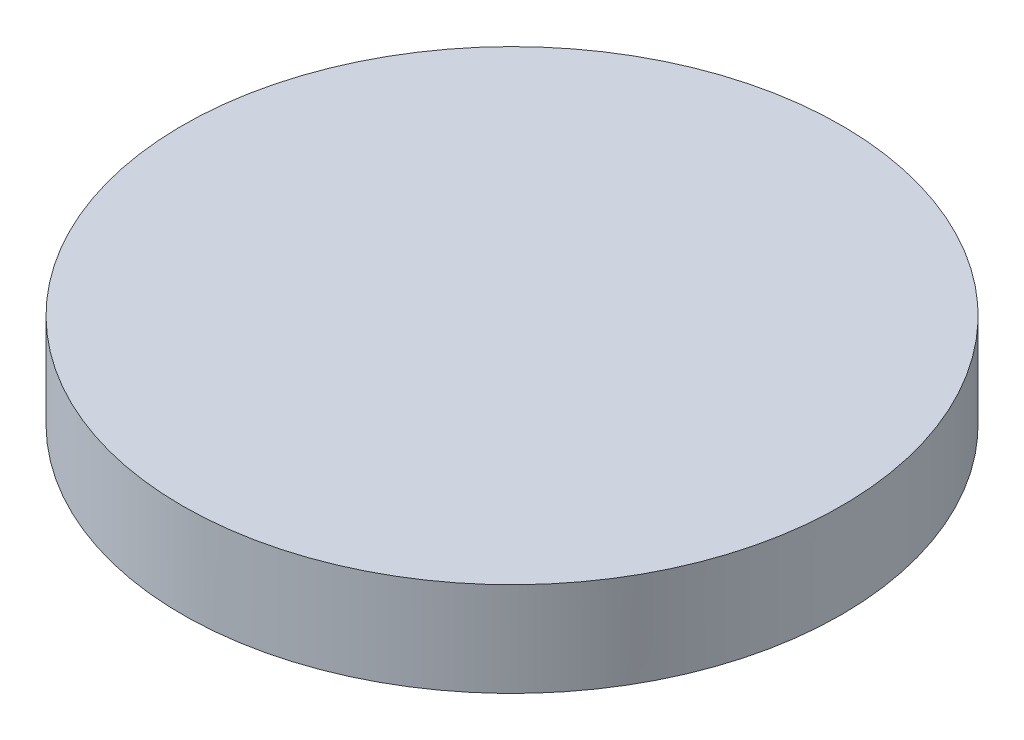
SolidWorks part; units mm, degrees
ref_plane "Front Plane" through (0, 0, 0) normal (0, 0, 1) x (1, 0, 0)
ref_plane "Top Plane" through (0, 0, 0) normal (0, 1, 0) x (1, 0, 0)
ref_plane "Right Plane" through (0, 0, 0) normal (1, 0, 0) x (0, 0, -1)
sketch "base" plane through (0, 0, 0) normal (0, 1, 0) x (1, 0, 0)
  circle A0 centre (0, 0) radius 28
extrude "extrusao_base" add sketch "base" along normal blind 8
sketch "corte_base" plane through (0, 0, 0) normal (0, 1, 0) x (1, 0, 0)
  circle A0 centre (0, 0) radius 26.5
extrude "extrusao_corte_base" cut sketch "corte_base" along normal blind 5
sketch "mid_line" plane through (0, 0, 0) normal (0, 1, 0) x (1, 0, 0)
  line L0 (-64.917, 0) -> (69.5719, 0) construction
ref_plane "Plane2" through (0, 0, 0) normal (0, 0, 1) x (1, 0, 0)
sketch "usb" plane through (0, 0, 0) normal (0, 1, 0) x (1, 0, 0)
  line L0 (-73.9689, 0) -> (73.9689, 0) construction
  line L1 (-142.5267, 5.1) -> (0, 5.1)
  line L2 (-142.5267, 5.1) -> (-142.5267, -5.1)
  line L3 (-142.5267, -5.1) -> (0, -5.1)
  line L4 (0, 5.1) -> (0, -5.1)
  line L5 (-142.5267, 5.1) -> (0, -5.1) construction
  line L6 (-142.5267, -5.1) -> (0, 5.1) construction
  point P0 (-71.2633, 0)
extrude "corte_usb" cut sketch "usb" along normal blind 5
sketch "suporte" plane through (0, 0, 0) normal (0, 1, 0) x (1, 0, 0)
  circle A0 centre (-11.22, -13.02) radius 0.75
extrude "extrusao_suporte" add sketch "suporte" against normal blind 2 from surface at 5 separate body starting at face at (-13.7591, 5, 0)
